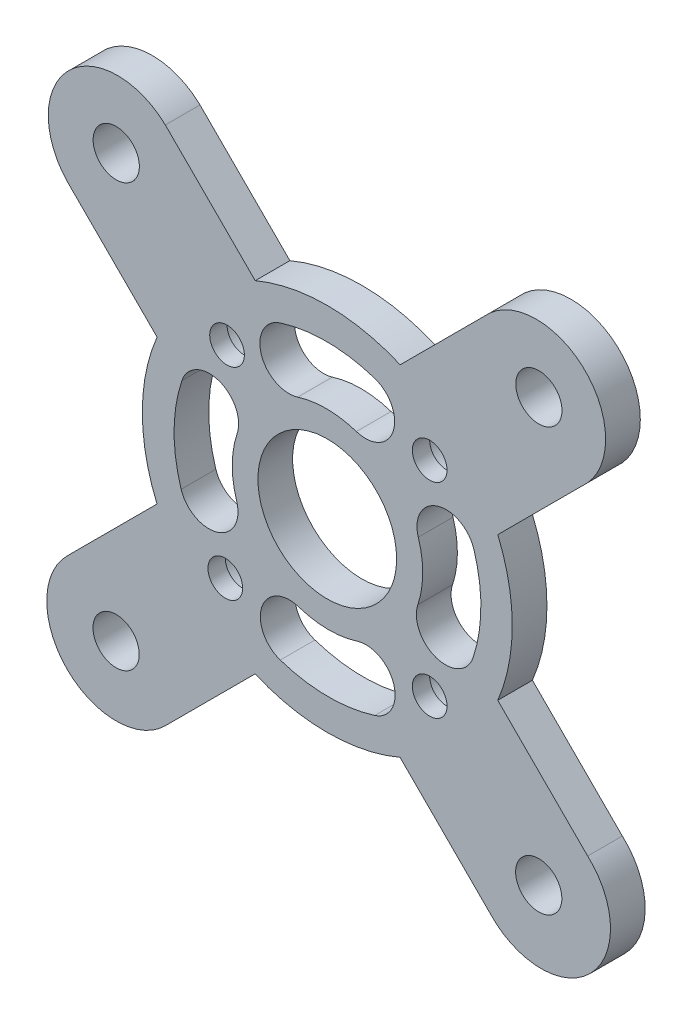
SolidWorks part; units mm, degrees
ref_plane "Plano frontal" through (0, 0, 0) normal (0, 0, 1) x (1, 0, 0)
ref_plane "Plano superior" through (0, 0, 0) normal (0, 1, 0) x (1, 0, 0)
ref_plane "Plano direito" through (0, 0, 0) normal (1, 0, 0) x (0, 0, -1)
sketch "Esboço1" plane through (0, 0, 0) normal (0, 0, 1) x (1, 0, 0)
  line L0 (22.5097, 13.9879) -> (14.7316, 6.2097)
  line L1 (14.0663, 22.4908) -> (6.2881, 14.7126)
  line L2 (-14.0286, 22.5216) -> (-6.2504, 14.7435)
  line L3 (-22.519, 14.0484) -> (-14.7408, 6.2702)
  line L4 (14.0531, -22.4815) -> (6.275, -14.7033)
  line L5 (22.5058, -13.9824) -> (14.7276, -6.2042)
  line L6 (-22.5263, -14.0162) -> (-14.7481, -6.238)
  line L7 (-14.041, -22.5014) -> (-6.2629, -14.7233)
  line L8 (-18.1526, 18.1636) -> (-8.6896, 8.7006) construction
  arc A1 (-3.3324, 10.257) -> (3.2912, 10.2056) centre (-0.1, 0) cw construction
  circle A2 centre (-0.0174, 0.0075) radius 6
  arc A3 (-6.2629, -14.7233) -> (6.275, -14.7033) centre (-0.0174, 0.0075) ccw
  arc A4 (-22.519, 14.0484) -> (-14.0286, 22.5216) centre (-18.1526, 18.1636) cw
  arc A6 (14.0663, 22.4908) -> (22.5097, 13.9879) centre (18.061, 18.0139) cw
  arc A8 (22.5058, -13.9824) -> (14.0531, -22.4815) centre (18.4798, -18.4312) cw
  arc A10 (-14.041, -22.5014) -> (-22.5263, -14.0162) centre (-18.2837, -18.2588) cw
  arc A16 (4.0849, 12.5942) -> (-4.0889, 12.6577) centre (-0.1, 0) ccw
  arc A17 (2.4975, 7.8169) -> (-2.5758, 7.8563) centre (-0.1, 0) ccw
  arc A18 (2.4975, 7.8169) -> (4.0849, 12.5942) centre (3.2912, 10.2056) ccw
  arc A19 (-4.0889, 12.6577) -> (-2.5758, 7.8563) centre (-3.3324, 10.257) ccw
  arc A20 (10.257, 3.3324) -> (10.2056, -3.2912) centre (0, 0.1) cw construction
  arc A21 (12.5942, -4.0849) -> (12.6577, 4.0889) centre (0, 0.1) ccw
  arc A22 (7.8169, -2.4975) -> (7.8563, 2.5758) centre (0, 0.1) ccw
  arc A23 (7.8169, -2.4975) -> (12.5942, -4.0849) centre (10.2056, -3.2912) ccw
  arc A24 (12.6577, 4.0889) -> (7.8563, 2.5758) centre (10.257, 3.3324) ccw
  arc A25 (3.3324, -10.257) -> (-3.2912, -10.2056) centre (0.1, 0) cw construction
  arc A26 (-4.0849, -12.5942) -> (4.0889, -12.6577) centre (0.1, 0) ccw
  arc A27 (-2.4975, -7.8169) -> (2.5758, -7.8563) centre (0.1, 0) ccw
  arc A28 (-2.4975, -7.8169) -> (-4.0849, -12.5942) centre (-3.2912, -10.2056) ccw
  arc A29 (4.0889, -12.6577) -> (2.5758, -7.8563) centre (3.3324, -10.257) ccw
  arc A30 (-10.257, -3.3324) -> (-10.2056, 3.2912) centre (0, -0.1) cw construction
  arc A31 (-12.5942, 4.0849) -> (-12.6577, -4.0889) centre (0, -0.1) ccw
  arc A32 (-7.8169, 2.4975) -> (-7.8563, -2.5758) centre (0, -0.1) ccw
  arc A33 (-7.8169, 2.4975) -> (-12.5942, 4.0849) centre (-10.2056, 3.2912) ccw
  arc A34 (-12.6577, -4.0889) -> (-7.8563, -2.5758) centre (-10.257, -3.3324) ccw
  arc A35 (-14.7408, 6.2702) -> (-14.7481, -6.238) centre (-0.0174, 0.0075) ccw
  arc A36 (6.2881, 14.7126) -> (-6.2504, 14.7435) centre (-0.0174, 0.0075) ccw
  arc A37 (14.7276, -6.2042) -> (14.7316, 6.2097) centre (-0.0174, 0.0075) ccw
  point P9 (-0.0165, 10.7539)
  point P10 (-18.3813, 18.3813)
  point P34 (0, 0)
  point P43 (0, 0)
  point P52 (10.7539, 0.0165)
  point P60 (0.0165, -10.7539)
  point P68 (-10.7539, -0.0165)
  point P74 (0, 0)
extrude "Ressalto-extrusão1" add sketch "Esboço1" along normal blind 3
sketch "Esboço3" plane through (0, 0, 0) normal (0, 0, -1) x (-1, 0, 0)
  circle A0 centre (-18.285, 18.2738) radius 2
  circle A1 centre (18.2738, 18.285) radius 2
  circle A2 centre (18.285, -18.2738) radius 2
  circle A3 centre (-18.2738, -18.285) radius 2
  point P4 (18.2738, 18.285)
  point P6 (18.285, -18.2738)
  point P7 (-18.2738, -18.285)
  point P8 (-18.285, 18.2738)
  point P9 (0, 0)
  dimension "D2" = 4
  dimension "D1" = 4
sketch "Esboço5" plane through (0, 0, 0) normal (0, 0, -1) x (-1, 0, 0)
  point P0 (-8.8388, 8.8388)
  point P1 (8.6896, 8.7006)
  point P3 (8.8388, -8.8388)
  point P5 (-8.8388, -8.8388)
hole_wizard "Rebaixo para parafuso de máquina com cabeça panela de M22" positions "3DSketch3" profile "Esboço6" counterbore size "M2" standard "Ansi Metric" end condition through all
sketch3d "3DSketch3"
  point P0 (8.8388, 8.8388, 0)
  point P3 (-8.6896, 8.7006, 0)
  point P6 (-8.8388, -8.8388, 0)
  point P9 (8.8388, -8.8388, 0)
sketch "Esboço6" plane through (8.8388, 8.8388, 0) normal (1, 0, 0) x (0, 1, 0)
  line L0 (0, 0) -> (0, 3)
  line L1 (0, 3) -> (1.5, 3)
  line L3 (1.5, 3) -> (1.5, 1.5)
  line L4 (1.5, 1.5) -> (2.5, 1.5)
  line L5 (2.5, 1.5) -> (2.5, 0)
  line L7 (2.5, 0) -> (0, 0)
  line L11 (0, -6.35) -> (0, 107.95) construction
  dimension "Thru Hole Dia." = 3
  dimension "Thru Hole Depth" = 3
  dimension "C'Bore Dia." = 5
  dimension "C'Bore Depth" = 1.5
extrude "Corte-extrusão1" cut sketch "Esboço3" against normal through all
